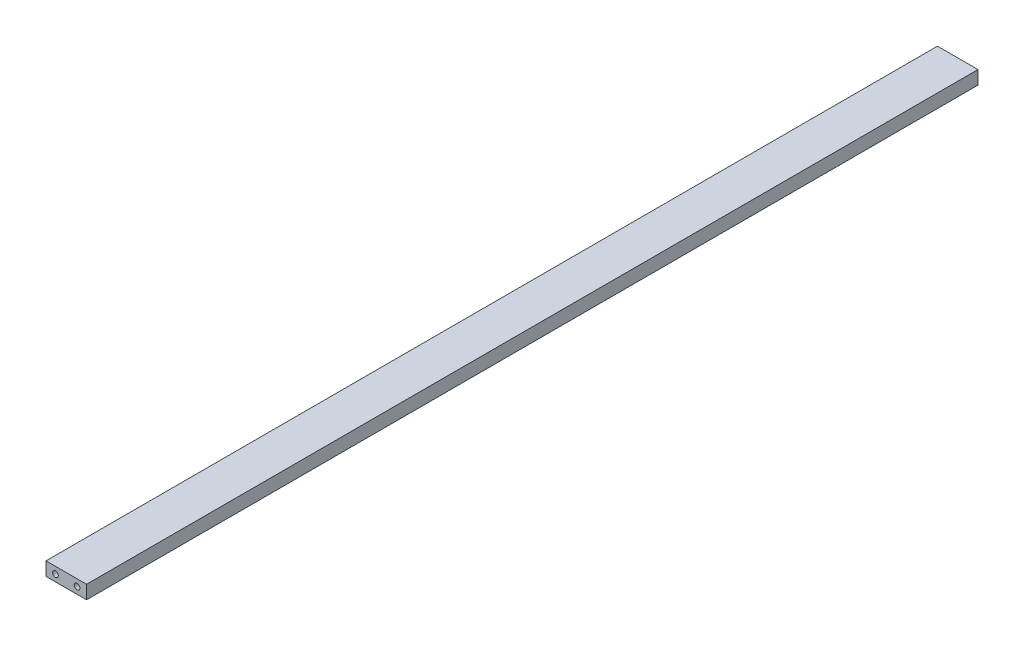
SolidWorks part; units mm, degrees
ref_plane "Front Plane" through (0, 0, 0) normal (0, 0, 1) x (1, 0, 0)
ref_plane "Top Plane" through (0, 0, 0) normal (0, 1, 0) x (1, 0, 0)
ref_plane "Right Plane" through (0, 0, 0) normal (1, 0, 0) x (0, 0, -1)
sketch "Sketch1" plane through (0, 0, 0) normal (0, 0, 1) x (1, 0, 0)
  line L1 (15, -5) -> (-15, -5)
  line L2 (15, -5) -> (15, 5)
  line L3 (15, 5) -> (-15, 5)
  line L4 (-15, -5) -> (-15, 5)
  line L5 (15, -5) -> (-15, 5) construction
  line L6 (15, 5) -> (-15, -5) construction
  point P0 (0, 0)
  dimension "D1" = 30
  dimension "D2" = 10
extrude "Boss-Extrude1" add sketch "Sketch1" along normal blind 660
sketch "Sketch2" plane through (0, 0, 0) normal (0, 0, -1) x (-1, 0, 0)
  line L0 (0, 5) -> (0, -4.8696) construction
  line L1 (-15, 5) -> (15, 5) construction
  line L2 (-15, 0) -> (15, 0) construction
  line L3 (-15, -5) -> (-15, 5) construction
  line L4 (15, 5) -> (15, -5) construction
  point P11 (8, 0)
  point P12 (-8, 0)
  dimension "D1" = 8
hole_wizard "M5 Tapped Hole1" positions "3DSketch1" profile "Sketch3" tap size "M5" standard "ISO"
sketch3d "3DSketch1"
  point P0 (-8, 0, 0)
  point P3 (8, 0, 0)
sketch "Sketch3" plane through (-8, 0, 0) normal (1, 0, 0) x (0, 1, 0)
  line L0 (0, 0) -> (0, 18.6618)
  line L1 (0, 18.6618) -> (2.1, 17.4)
  line L2 (2.1, 17.4) -> (2.1, 0)
  line L5 (2.1, 0) -> (0, 0)
  line L10 (0, 18.6618) -> (-2.1, 17.4) construction
  line L11 (0, -6.35) -> (0, 107.95) construction
  dimension "Tap Drill Dia." = 4.2
  dimension "Tap Drill Depth" = 17.4
  dimension "Drill Angle" = 118
sketch "Sketch4" plane through (0, 0, 660) normal (0, 0, 1) x (1, 0, 0)
  line L0 (0, 5) -> (0, -5) construction
  line L1 (-15, -5) -> (15, -5) construction
  line L2 (15, 0) -> (-15, 0) construction
  point P9 (8, 0)
  point P10 (-8, 0)
hole_wizard "M5 Tapped Hole2" positions "3DSketch2" profile "Sketch5" tap size "M5" standard "ISO"
sketch3d "3DSketch2"
  point P0 (-8, 0, 0)
  point P3 (8, 0, 0)
sketch "Sketch5" plane through (-8, 0, 0) normal (1, 0, 0) x (0, 1, 0)
  line L0 (0, 0) -> (0, 18.6618)
  line L1 (0, 18.6618) -> (2.1, 17.4)
  line L2 (2.1, 17.4) -> (2.1, 0)
  line L5 (2.1, 0) -> (0, 0)
  line L10 (0, 18.6618) -> (-2.1, 17.4) construction
  line L11 (0, -6.35) -> (0, 107.95) construction
  dimension "Tap Drill Dia." = 4.2
  dimension "Tap Drill Depth" = 17.4
  dimension "Drill Angle" = 118
hole_wizard "M5 Tapped Hole3" positions "3DSketch3" profile "Sketch6" tap size "M5" standard "ISO"
sketch3d "3DSketch3"
  point P0 (-8, 0, 660)
  point P3 (8, 0, 660)
sketch "Sketch6" plane through (-8, 0, 660) normal (1, 0, 0) x (0, -1, 0)
  line L0 (0, 0) -> (0, 18.6618)
  line L1 (0, 18.6618) -> (2.1, 17.4)
  line L2 (2.1, 17.4) -> (2.1, 0)
  line L5 (2.1, 0) -> (0, 0)
  line L10 (0, 18.6618) -> (-2.1, 17.4) construction
  line L11 (0, -6.35) -> (0, 107.95) construction
  dimension "Tap Drill Dia." = 4.2
  dimension "Tap Drill Depth" = 17.4
  dimension "Drill Angle" = 118
